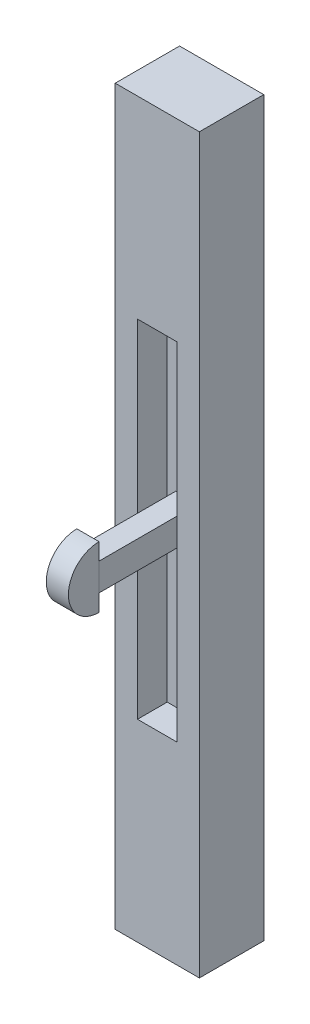
SolidWorks part; units mm, degrees
ref_plane "Front Plane" through (0, 0, 0) normal (1, 0, 0) x (0, 1, 0)
ref_plane "Top Plane" through (0, 0, 0) normal (0, 0, 1) x (0, 1, 0)
ref_plane "Right Plane" through (0, 0, 0) normal (0, 1, 0) x (-1, 0, 0)
sketch "Sketch1" plane through (0, 0, 0) normal (0, 0, 1) x (0, 1, 0)
  line L1 (-37, -4.25) -> (37, -4.25)
  line L2 (-37, -4.25) -> (-37, 4.25)
  line L3 (-37, 4.25) -> (37, 4.25)
  line L4 (37, -4.25) -> (37, 4.25)
  line L5 (-37, -4.25) -> (37, 4.25) construction
  line L6 (-37, 4.25) -> (37, -4.25) construction
  point P0 (0, 0)
extrude "Boss-Extrude1" add sketch "Sketch1" along normal blind 6.5
sketch "Sketch2" plane through (0, 0, 6.5) normal (0, 0, 1) x (1, 0, 0)
  line L1 (-2, -17.5) -> (2, -17.5)
  line L2 (-2, -17.5) -> (-2, 17.5)
  line L3 (-2, 17.5) -> (2, 17.5)
  line L4 (2, -17.5) -> (2, 17.5)
  line L5 (-2, -17.5) -> (2, 17.5) construction
  line L6 (-2, 17.5) -> (2, -17.5) construction
  point P0 (0, 0)
extrude "Cut-Extrude1" cut sketch "Sketch2" against normal blind 3
sketch "Sketch3" plane through (0, 0, 3.5) normal (0, 0, 1) x (1, 0, 0)
  line L1 (-1.1214, -1.3912) -> (1.1214, -1.3912)
  line L2 (-1.1214, -1.3912) -> (-1.1214, 1.3912)
  line L3 (-1.1214, 1.3912) -> (1.1214, 1.3912)
  line L4 (1.1214, -1.3912) -> (1.1214, 1.3912)
  line L5 (-1.1214, -1.3912) -> (1.1214, 1.3912) construction
  line L6 (-1.1214, 1.3912) -> (1.1214, -1.3912) construction
  point P0 (0, 0)
extrude "Boss-Extrude2" add sketch "Sketch3" along normal blind 10
sketch "Sketch4" plane through (0, 0, 0) normal (1, 0, 0) x (0, 1, 0)
  line L0 (-1.3912, 13.5) -> (1.3912, 13.5) construction
  line L1 (-3.0931, 13.5) -> (3.0931, 13.5)
  arc A0 (-3.0931, 13.5) -> (3.0931, 13.5) centre (0, 13.5) cw
extrude "Boss-Extrude3" add sketch "Sketch4" along normal blind 1.12 contours A0 L1
ref_plane "Plane1" through (0, 3.0931, 13.5) normal (0, 0, -1) x (0, 1, 0)
sketch "Sketch8" plane through (0, 0, 0) normal (-1, 0, 0) x (0, -1, 0)
  line L0 (-1.3912, 13.5) -> (1.3912, 13.5) construction
  line L1 (-58.0931, 13.5) -> (51.9069, 13.5) construction
  line L2 (3.0931, 13.5) -> (1.3912, 13.5) construction
  line L3 (-3.0931, 13.5) -> (3.0931, 13.5)
  arc A0 (3.0931, 13.5) -> (-3.0931, 13.5) centre (0, 13.5) ccw
sketch "Sketch10" plane through (0, 0, 0) normal (-1, 0, 0) x (0, -1, 0)
  line L0 (3.0931, 13.5) -> (-3.0931, 13.5)
  arc A0 (-3.0931, 13.5) -> (3.0931, 13.5) centre (0, 13.5) cw
  arc A1 (3.0931, 13.5) -> (-3.0931, 13.5) centre (0, 13.5) ccw construction
extrude "Boss-Extrude5" add sketch "Sketch10" along normal blind 1.12
